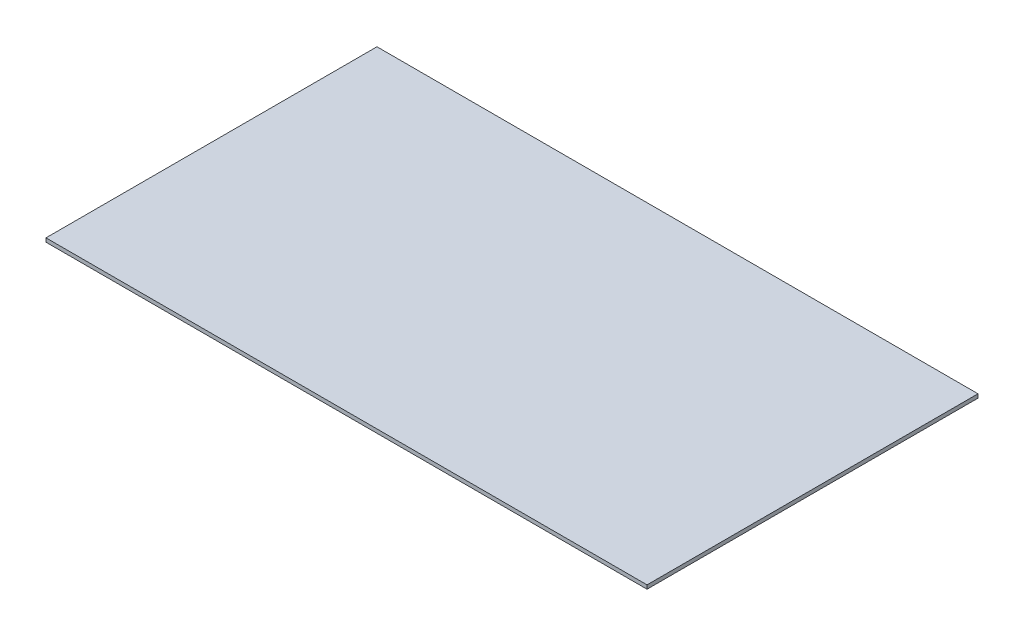
SolidWorks part; units mm, degrees
material "Сосна"
ref_plane "Спереди" through (0, 0, 0) normal (0, 0, 1) x (1, 0, 0)
ref_plane "Сверху" through (0, 0, 0) normal (0, 1, 0) x (1, 0, 0)
ref_plane "Справа" through (0, 0, 0) normal (1, 0, 0) x (0, 0, -1)
sketch "Эскиз1" plane through (0, 0, 0) normal (0, 0, 1) x (1, 0, 0)
  line L0 (-1575, 40) -> (-1575, 0) construction
  line L1 (0, 40) -> (-1580, 40)
  line L2 (0, 40) -> (0, 50)
  line L3 (0, 50) -> (-1580, 50)
  line L4 (-1580, 40) -> (-1580, 50)
  dimension "D1" = 10
  dimension "D2" = 5
extrude "Бобышка-Вытянуть1" add sketch "Эскиз1" against normal up to surface (870 mm away)
